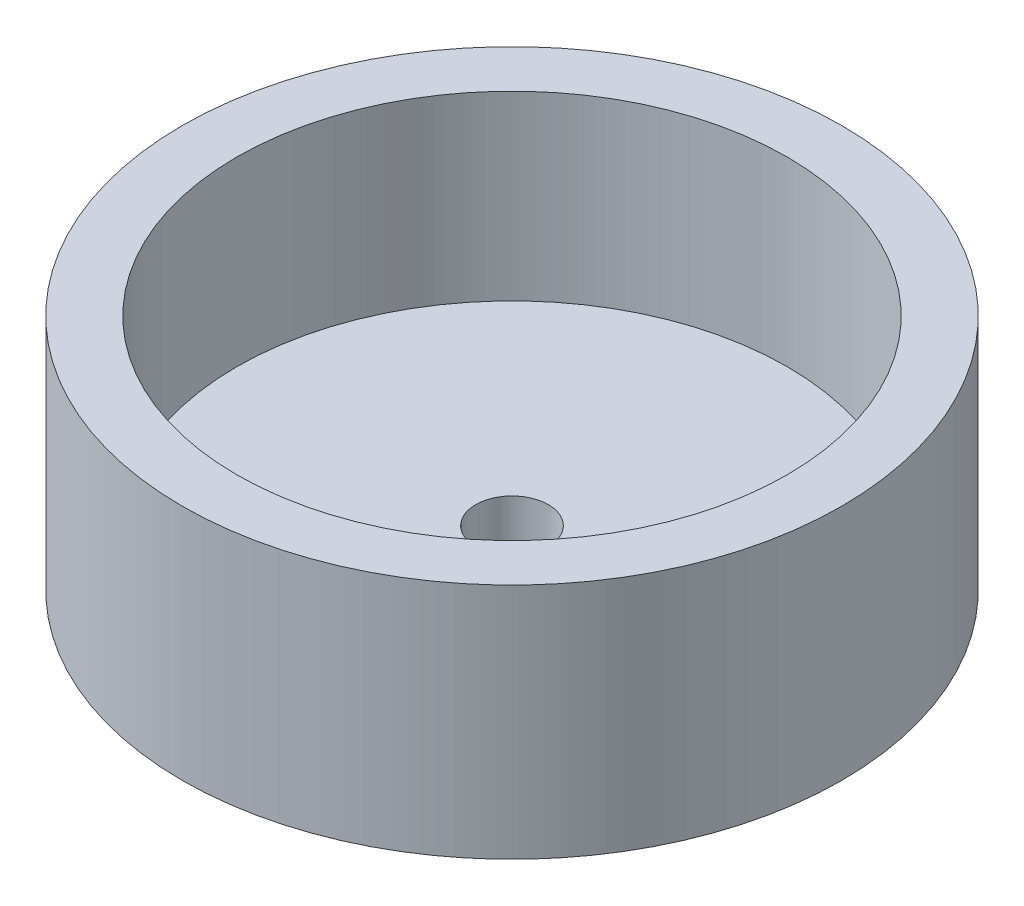
SolidWorks part; units mm, degrees
ref_plane "前视基准面" through (0, 0, 0) normal (0, 0, 1) x (1, 0, 0)
ref_plane "上视基准面" through (0, 0, 0) normal (0, 1, 0) x (1, 0, 0)
ref_plane "右视基准面" through (0, 0, 0) normal (1, 0, 0) x (0, 0, -1)
other "Configuration Table"
sketch "草图1" plane through (0, 0, 0) normal (0, 1, 0) x (1, 0, 0)
  circle A0 centre (0, 0) radius 19.7
  circle A1 centre (0, 0) radius 2.6
  circle A2 centre (0, 0) radius 23.6
  dimension "D1" = 39.4
  dimension "D2" = 5.2
  dimension "D3" = 47.2
extrude "凸台-拉伸1" add sketch "草图1" along normal blind 4 contours A2 A0 | A0 A1
sketch "草图2" plane through (0, 4, 0) normal (0, 1, 0) x (1, 0, 0)
  circle A1 centre (0, 0) radius 23.6
  circle A2 centre (0, 0) radius 23.6
  circle A3 centre (0, 0) radius 2.6
  circle A4 centre (0, 0) radius 2.6
  circle A5 centre (0, 0) radius 19.7
  circle A6 centre (0, 0) radius 19.7
  circle M4 centre (0, 0) radius 23.6
  dimension "D1" = 0
  dimension "D2" = 0
  dimension "D3" = 0
extrude "凸台-拉伸2" add sketch "草图2" along normal blind 13 contours A6 M4
